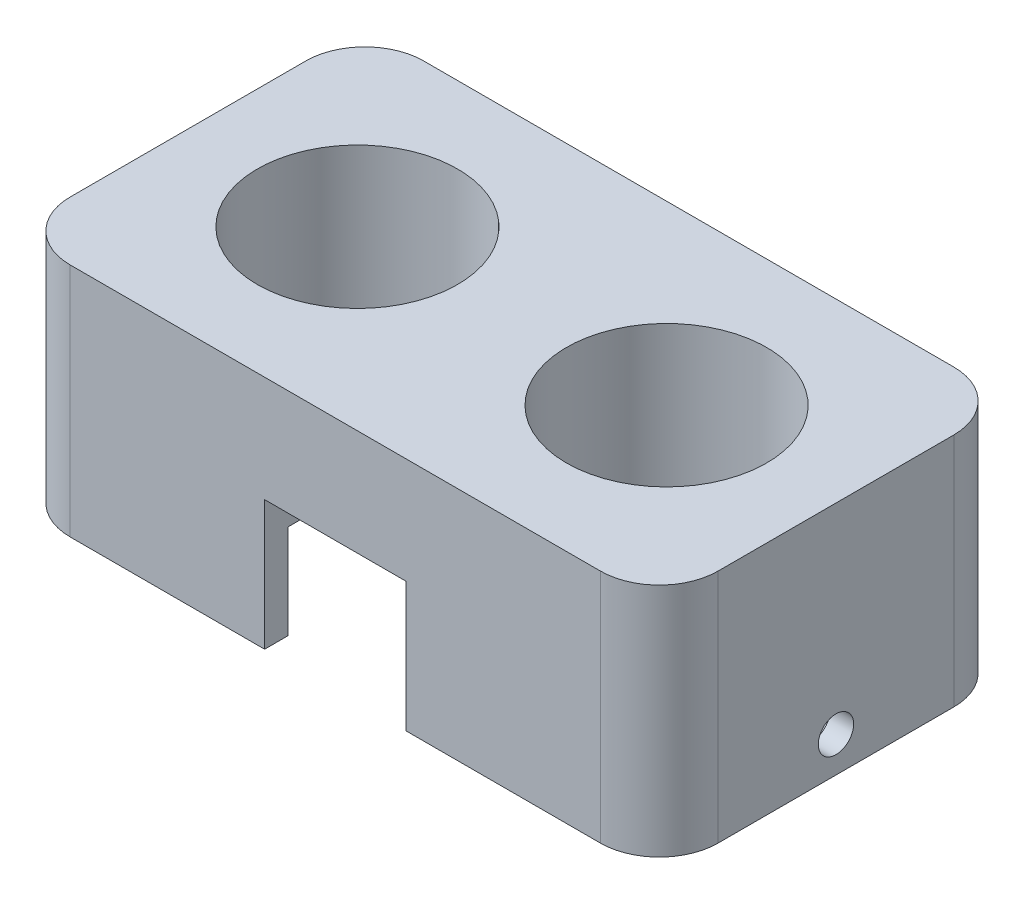
SolidWorks part; units mm, degrees
ref_plane "Front Plane" through (0, 0, 0) normal (0, 0, 1) x (1, 0, 0)
ref_plane "Top Plane" through (0, 0, 0) normal (0, 1, 0) x (1, 0, 0)
ref_plane "Right Plane" through (0, 0, 0) normal (1, 0, 0) x (0, 0, -1)
sketch "Sketch1" plane through (0, 0, 0) normal (0, 1, 0) x (1, 0, 0)
  line L1 (-27.5, -15) -> (27.5, -15)
  line L2 (-27.5, -15) -> (-27.5, 15)
  line L3 (-27.5, 15) -> (27.5, 15)
  line L4 (27.5, -15) -> (27.5, 15)
  line L5 (-27.5, -15) -> (27.5, 15) construction
  line L6 (-27.5, 15) -> (27.5, -15) construction
  point P0 (0, 0)
  dimension "D1" = 30
  dimension "D2" = 55
extrude "Boss-Extrude1" add sketch "Sketch1" along normal blind 12
sketch "Sketch2" plane through (0, 12, 0) normal (0, 1, 0) x (1, 0, 0)
  line L0 (0, 3.5755) -> (0, -2.1377) construction
  line L1 (0, 0) -> (-13.12, 0) construction
  circle A0 centre (-13.12, 0) radius 8.5
  circle A1 centre (13.12, 0) radius 8.5
  circle A2 centre (-13.12, 0) radius 10.5
  circle A3 centre (13.12, 0) radius 10.5
  dimension "D1" = 17
  dimension "D3" = 2
  dimension "D2" = 26.24
extrude "Cut-Extrude1" cut sketch "Sketch2" against normal through all contours A0 | A1
sketch "Sketch4" plane through (0, 0, 0) normal (0, -1, 0) x (1, 0, 0)
  line L0 (0, -15) -> (0, -7.5) construction
  line L2 (27.5, -15) -> (-27.5, -15) construction
  line L3 (6, -10) -> (-6, -10)
  line L4 (6, -10) -> (6, -5)
  line L5 (6, -5) -> (-6, -5)
  line L6 (-6, -10) -> (-6, -5)
  line L7 (6, -10) -> (-6, -5) construction
  line L8 (6, -5) -> (-6, -10) construction
  dimension "D1" = 12
  dimension "D2" = 5
  dimension "D3" = 5
extrude "Cut-Extrude2" cut sketch "Sketch4" against normal blind 5
fillet "Fillet1" radius 2 4 edges at (6, 2.5, -5) (-6, 2.5, -5) (-6, 2.5, -10) (6, 2.5, -10)
sketch "Sketch5" plane through (0, 0, 0) normal (0, -1, 0) x (1, 0, 0)
  line L0 (-27.5, 15) -> (27.5, 15) construction
  line L1 (-6, 10) -> (6, 10)
  line L2 (-6, 10) -> (-6, 15)
  line L3 (-6, 15) -> (6, 15)
  line L4 (6, 10) -> (6, 15)
  line L5 (-6, 10) -> (6, 15) construction
  line L6 (-6, 15) -> (6, 10) construction
  line L7 (0, 12.5) -> (0, 15) construction
  point P0 (0, 12.5)
  dimension "D1" = 12
  dimension "D2" = 5
extrude "Cut-Extrude3" cut sketch "Sketch5" against normal blind 3
fillet "Fillet2" radius 5 4 edges at (27.5, 6, 15) (-27.5, 6, -15) (27.5, 6, -15) (-27.5, 6, 15)
sketch "Sketch6" plane through (0, 0, 0) normal (0, -1, 0) x (1, 0, 0)
  line L8 (25.5, -10) -> (25.5, 10)
  line L9 (22.5, 13) -> (8, 13)
  line L13 (-8, 13) -> (-22.5, 13)
  line L14 (-25.5, 10) -> (-25.5, -10)
  line L15 (-22.5, -13) -> (22.5, -13)
  line L16 (27.5, -10) -> (27.5, 10)
  line L17 (22.5, 15) -> (6, 15)
  line L18 (6, 15) -> (6, 10)
  line L19 (6, 10) -> (-6, 10)
  line L20 (-6, 10) -> (-6, 15)
  line L21 (-6, 15) -> (-22.5, 15)
  line L22 (-27.5, 10) -> (-27.5, -10)
  line L23 (-22.5, -15) -> (22.5, -15)
  line L24 (27.5, -10) -> (27.5, 10)
  line L25 (22.5, 15) -> (6, 15)
  line L26 (6, 15) -> (6, 10)
  line L27 (6, 10) -> (-6, 10)
  line L28 (-6, 10) -> (-6, 15)
  line L29 (-6, 15) -> (-22.5, 15)
  line L30 (-27.5, 10) -> (-27.5, -10)
  line L31 (-22.5, -15) -> (22.5, -15)
  line L32 (-8, 8) -> (-8, 13) construction
  line L33 (8, 8) -> (-8, 8) construction
  line L34 (8, 13) -> (8, 8) construction
  line L35 (-8, 13) -> (-6, 13)
  line L36 (0, 16.6951) -> (0, 15.068) construction
  line L37 (8, 13) -> (6, 13)
  arc A4 (25.5, 10) -> (22.5, 13) centre (22.5, 10) ccw
  arc A5 (-22.5, 13) -> (-25.5, 10) centre (-22.5, 10) ccw
  arc A6 (-25.5, -10) -> (-22.5, -13) centre (-22.5, -10) ccw
  arc A7 (22.5, -13) -> (25.5, -10) centre (22.5, -10) ccw
  arc A8 (27.5, 10) -> (22.5, 15) centre (22.5, 10) ccw
  arc A9 (-22.5, 15) -> (-27.5, 10) centre (-22.5, 10) ccw
  arc A10 (-27.5, -10) -> (-22.5, -15) centre (-22.5, -10) ccw
  arc A11 (22.5, -15) -> (27.5, -10) centre (22.5, -10) ccw
  arc A12 (27.5, 10) -> (22.5, 15) centre (22.5, 10) ccw
  arc A13 (-22.5, 15) -> (-27.5, 10) centre (-22.5, 10) ccw
  arc A14 (-27.5, -10) -> (-22.5, -15) centre (-22.5, -10) ccw
  arc A15 (22.5, -15) -> (27.5, -10) centre (22.5, -10) ccw
  line M15 (27.5, -10) -> (27.5, 10)
  arc M16 (27.5, 10) -> (22.5, 15) centre (22.5, 10) ccw
  line M17 (22.5, 15) -> (6, 15)
  line M18 (6, 15) -> (6, 10)
  line M21 (-6, 15) -> (-22.5, 15)
  arc M22 (-22.5, 15) -> (-27.5, 10) centre (-22.5, 10) ccw
  line M23 (-27.5, 10) -> (-27.5, -10)
  arc M24 (-27.5, -10) -> (-22.5, -15) centre (-22.5, -10) ccw
  line M25 (-22.5, -15) -> (22.5, -15)
  arc M26 (22.5, -15) -> (27.5, -10) centre (22.5, -10) ccw
  dimension "D1" = 0
  dimension "D2" = 2
extrude "Boss-Extrude3" add sketch "Sketch6" along normal blind 8 contours A7 L15 A6 L14 A5 L13 L35 L28 L37 L9 A4 L8 M21 M22 M23 M24 M25 M26 M15 M16 M17 M18
hole_wizard "Ø3.0mm Dowel Hole1" positions "Sketch7" profile "Sketch9" hole size "Ø3.0" standard "ANSI Metric" end condition through all
sketch "Sketch7" plane through (-27.5, 0, 0) normal (-1, 0, 0) x (0, 0, 1)
  line L0 (0, -8) -> (0, -5) construction
  line L2 (10, -8) -> (-10, -8) construction
  point P2 (0, -5)
  dimension "D1" = 3
sketch "Sketch9" plane through (-27.5, -5, 0) normal (0, 1, 0) x (0, 0, 1)
  line L0 (0, 0) -> (0, 55)
  line L1 (0, 55) -> (1.5, 55)
  line L2 (1.5, 55) -> (1.5, 0)
  line L5 (1.5, 0) -> (0, 0)
  line L11 (0, -6.35) -> (0, 107.95) construction
  dimension "Thru Hole Dia." = 3
  dimension "Thru Hole Depth" = 55
sketch "Sketch10" plane through (25.5, 0, 0) normal (-1, 0, 0) x (0, 0, 1)
  line L0 (-10, 0) -> (10, 0) construction
  line L1 (2.7713, -5) -> (1.3856, -2.6)
  line L2 (1.3856, -2.6) -> (-1.3856, -2.6)
  line L3 (-1.3856, -2.6) -> (-2.7713, -5)
  line L4 (-2.7713, -5) -> (-1.3856, -7.4)
  line L5 (-1.3856, -7.4) -> (1.3856, -7.4)
  line L6 (1.3856, -7.4) -> (2.7713, -5)
  line L7 (4, -8) -> (-4, -8)
  line L8 (4, -8) -> (4, 0)
  line L9 (4, 0) -> (-4, 0)
  line L10 (-4, -8) -> (-4, 0)
  line L11 (4, -8) -> (-4, 0) construction
  line L12 (4, 0) -> (-4, -8) construction
  line L13 (-10, -8) -> (10, -8) construction
  line L14 (0, -4) -> (0, -5) construction
  circle A0 centre (0, -5) radius 2.4 construction
  point P1 (0, -4)
  dimension "D1" = 4.8
  dimension "D2" = 8
extrude "Boss-Extrude4" add sketch "Sketch10" along normal blind 2
mirror "Mirror1" about plane through (0, 0, 0) normal (1, 0, 0) of "Boss-Extrude4"
hole_wizard "Ø2.0 (2) Diameter Hole1" positions "Sketch11" profile "Sketch12" hole size "Ø2.0" standard "ANSI Metric"
sketch "Sketch11" plane through (0, 0, 0) normal (0, -1, 0) x (-1, 0, 0)
  point P0 (-21.425, 8.7)
  point P3 (21.425, 8.7)
  point P6 (21.425, -8.7)
  point P9 (-21.425, -8.7)
sketch "Sketch12" plane through (21.425, 0, -8.7) normal (1, 0, 0) x (0, 0, -1)
  line L0 (0, 0) -> (0, 10.6009)
  line L1 (0, 10.6009) -> (1, 10)
  line L2 (1, 10) -> (1, 0)
  line L5 (1, 0) -> (0, 0)
  line L10 (0, 10.6009) -> (-1, 10) construction
  line L11 (0, -6.35) -> (0, 107.95) construction
  dimension "Hole Dia." = 2
  dimension "Hole Depth" = 10
  dimension "Drill Angle" = 118
